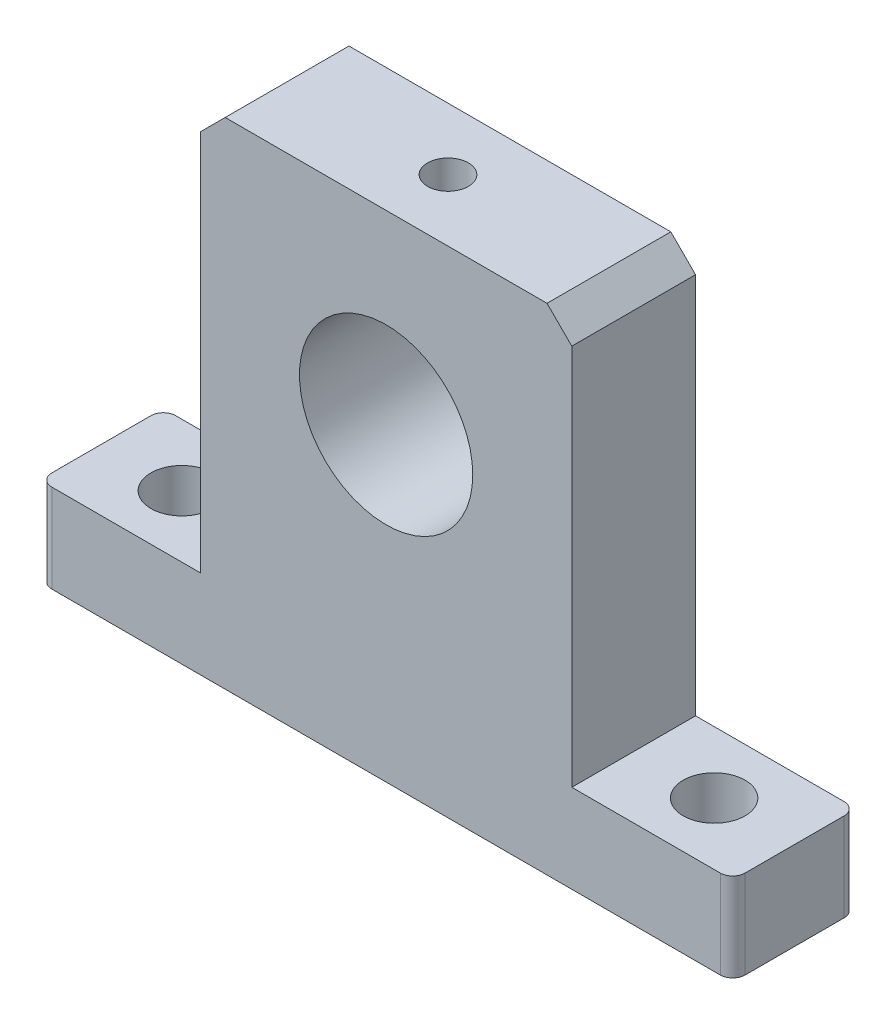
SolidWorks part; units mm, degrees
ref_plane "Front Plane" through (0, 0, 0) normal (0, 0, 1) x (1, 0, 0)
ref_plane "Top Plane" through (0, 0, 0) normal (0, 1, 0) x (1, 0, 0)
ref_plane "Right Plane" through (0, 0, 0) normal (1, 0, 0) x (0, 0, -1)
ref_plane "Plane1" through (0, 0, 10) normal (0, 0, 1) x (1, 0, 0)
sketch "Sketch1" plane through (0, 0, 10) normal (0, 0, 1) x (1, 0, 0)
  line L0 (-38.5903, -2.511) -> (17.4097, -2.511)
  line L1 (17.4097, -2.511) -> (17.4097, 37.489)
  line L2 (17.4097, 37.489) -> (-38.5903, 37.489)
  line L3 (-38.5903, 37.489) -> (-38.5903, -2.511)
extrude "Boss-Extrude1" add sketch "Sketch1" against normal blind 10
sketch "Sketch2" plane through (0, 0, 0) normal (0, 0, -1) x (-1, 0, 0)
  line L0 (25.5903, 37.489) -> (25.5903, 4.6256)
  line L1 (25.5903, 4.6256) -> (38.5903, 4.6256)
  line L2 (38.5903, 4.6256) -> (38.5903, 37.489)
  line L3 (38.5903, 37.489) -> (25.5903, 37.489)
extrude "Cut-Extrude1" cut sketch "Sketch2" against normal through all
sketch "Sketch3" plane through (0, 0, 0) normal (0, 0, -1) x (-1, 0, 0)
  line L0 (-17.4097, 4.6256) -> (-4.4097, 4.6256)
  line L1 (-4.4097, 4.6256) -> (-4.4097, 37.489)
  line L2 (-4.4097, 37.489) -> (-17.4097, 37.489)
  line L3 (-17.4097, 37.489) -> (-17.4097, 4.6256)
extrude "Cut-Extrude2" cut sketch "Sketch3" against normal through all
hole_wizard "Ø14.0 (14) Diameter Hole1" positions "Sketch5" profile "Sketch4" hole size "Ø14.0" standard "ANSI Metric"
sketch "Sketch5" plane through (0, 0, 10) normal (0, 0, 1) x (1, 0, 0)
  point P0 (-10.5903, 22.489)
sketch "Sketch4" plane through (-10.5903, 22.489, 10) normal (1, 0, 0) x (0, -1, 0)
  line L0 (0, 0) -> (0, 10)
  line L1 (0, 10) -> (7, 10)
  line L2 (7, 10) -> (7, 0)
  line L5 (7, 0) -> (0, 0)
  line L11 (0, -6.35) -> (0, 107.95) construction
  dimension "Thru Hole Dia." = 14
  dimension "Thru Hole Depth" = 10
hole_wizard "Ø3.3 (3.3) Diameter Hole1" positions "Sketch7" profile "Sketch6" hole size "Ø3.3" standard "ANSI Metric"
sketch "Sketch7" plane through (0, 37.489, 0) normal (0, 1, 0) x (1, 0, 0)
  point P0 (-10.5903, -5)
sketch "Sketch6" plane through (-10.5903, 37.489, 5) normal (1, 0, 0) x (0, 0, 1)
  line L0 (0, 0) -> (0, 8)
  line L1 (0, 8) -> (1.65, 8)
  line L2 (1.65, 8) -> (1.65, 0)
  line L5 (1.65, 0) -> (0, 0)
  line L11 (0, -6.35) -> (0, 107.95) construction
  dimension "Thru Hole Dia." = 3.3
  dimension "Thru Hole Depth" = 8
hole_wizard "Ø5.0 (5) Diameter Hole1" positions "Sketch9" profile "Sketch8" hole size "Ø5.0" standard "ANSI Metric"
sketch "Sketch9" plane through (0, 4.6256, 0) normal (0, 1, 0) x (1, 0, 0)
  point P0 (-32.0903, -5)
  point P1 (10.9097, -5)
sketch "Sketch8" plane through (-32.0903, 4.6256, 5) normal (1, 0, 0) x (0, 0, 1)
  line L0 (0, 0) -> (0, 7.1366)
  line L1 (0, 7.1366) -> (2.5, 7.1366)
  line L2 (2.5, 7.1366) -> (2.5, 0)
  line L5 (2.5, 0) -> (0, 0)
  line L11 (0, -6.35) -> (0, 107.95) construction
  dimension "Thru Hole Dia." = 5
  dimension "Thru Hole Depth" = 7.1366
chamfer "Chamfer1" distance 2 angle 45 2 edges at (4.4097, 37.489, 5) (-25.5903, 37.489, 5)
fillet "Fillet1" radius 1 4 edges at (17.4097, 1.0573, 0) (-38.5903, 1.0573, 0) (17.4097, 1.0573, 10) (-38.5903, 1.0573, 10)
